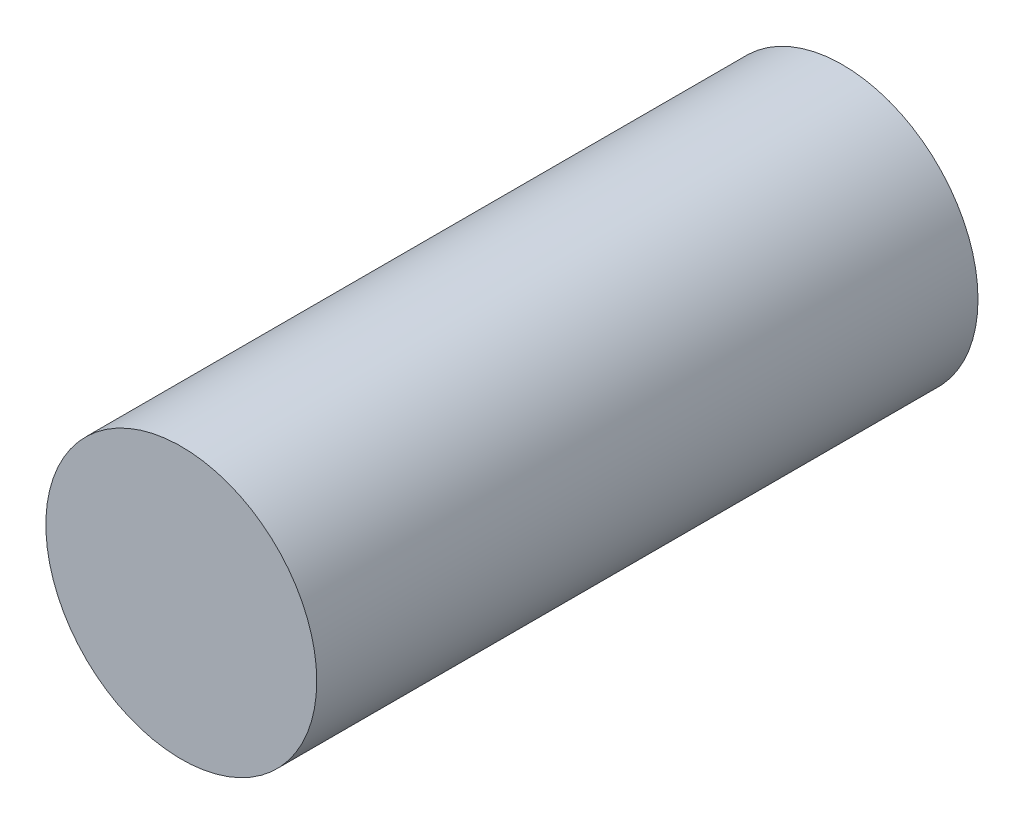
SolidWorks part; units mm, degrees
ref_plane "Front Plane" through (0, 0, 0) normal (0, 0, 1) x (1, 0, 0)
ref_plane "Top Plane" through (0, 0, 0) normal (0, 1, 0) x (1, 0, 0)
ref_plane "Right Plane" through (0, 0, 0) normal (1, 0, 0) x (0, 0, -1)
sketch "Planform" plane through (0, 0, 0) normal (0, 1, 0) x (1, 0, 0)
  line L0 (0, 0) -> (0, -7497.1177)
  line L1 (-17711.9405, -11444.2752) -> (-17711.9405, -14068.2664)
  line L2 (0, -1874.2794) -> (-17711.9405, -12100.273) construction
  line L3 (0, -1874.2794) -> (-6644.0672, -1874.2794) construction
  line L4 (0, 0) -> (-17711.9405, -11444.2752)
  line L5 (0, -7497.1177) -> (-17711.9405, -14068.2664)
  dimension "D1" = 7497.1177
  dimension "D2" = 2623.9912
  dimension "D3" = 1874.2794
  dimension "D4" = 655.9978
  dimension "D5" = 30
  dimension "D6" = 17711.9405
sketch "Sketch1" plane through (0, 0, 0) normal (0, 0, 1) x (1, 0, 0)
  circle A0 centre (0, 0) radius 1209.8064
  dimension "D1" = 2419.6129
extrude "Nacelle body" add sketch "Sketch1" along normal blind 5906.115
sketch "Black front" plane through (0, 0, 5906.115) normal (0, 0, 1) x (1, 0, 0)
  line L0 (59.2242, 1082.815) -> (229.8908, 1082.815) construction
sketch "Location" plane through (0, 0, 0) normal (0, 1, 0) x (1, 0, 0)
  line L0 (-1209.8064, -1506.8189) -> (1209.8064, -1506.8189)
  line L1 (1209.8064, 0) -> (-1209.8064, 0)
  line L2 (1209.8064, 0) -> (1209.8064, -5906.115)
  line L3 (1209.8064, -5906.115) -> (-1209.8064, -5906.115)
  line L4 (-1209.8064, 0) -> (-1209.8064, -5906.115)
  line L5 (-1209.8064, 0) -> (1209.8064, -5906.115)
  line L6 (1209.8064, 0) -> (-1209.8064, -5906.115)
  line L7 (1209.8064, -2953.0575) -> (-1209.8064, -2953.0575)
  point P9 (0, -1506.8189)
  point P11 (0, -2953.0575)
  dimension "D1" = 2419.6129
  dimension "D2" = 4399.2961
equation "\"Diameter\"= 7.938362438"
equation "\"Length\"= 19.37701766"
equation "\"D1@Sketch1\"=\"Diameter\""
equation "\"D1@Nacelle body\"=\"Length\""
equation "\"D2@Location\"=\"Diameter\"/1.1*2"
